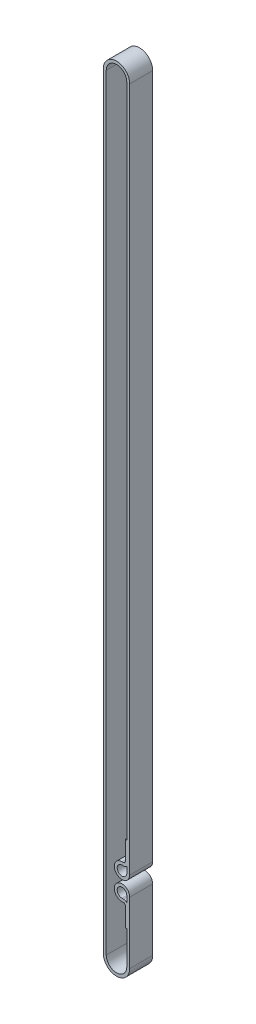
SolidWorks part; units mm, degrees
ref_plane "Front Plane" through (0, 0, 0) normal (0, 0, 1) x (1, 0, 0)
ref_plane "Top Plane" through (0, 0, 0) normal (0, 1, 0) x (1, 0, 0)
ref_plane "Right Plane" through (0, 0, 0) normal (1, 0, 0) x (0, 0, -1)
sketch "Sketch1" plane through (0, 0, 0) normal (0, 0, 1) x (1, 0, 0)
  line L0 (-6.365, 0) -> (-6.365, -400)
  line L1 (6.365, -400) -> (6.365, -367.7)
  line L2 (5.107, -382.704) -> (5.107, -372.704)
  line L3 (2.861, -357.7) -> (2.861, -367.7) construction
  line L4 (6.365, -357.7) -> (6.365, 0)
  line L5 (2.861, -371.204) -> (3.607, -371.204)
  line L6 (-997.139, -362.7) -> (49002.861, -362.7) construction
  line L7 (5.107, -342.696) -> (5.107, -352.696)
  line L8 (2.861, -354.196) -> (3.607, -354.196)
  arc A0 (6.365, 0) -> (-6.365, 0) centre (0, 0) ccw
  arc A1 (-6.365, -400) -> (6.365, -400) centre (0, -400) ccw
  circle A2 centre (2.861, -367.7) radius 2.5 construction
  arc A3 (6.365, -367.7) -> (2.861, -371.204) centre (2.861, -367.7) ccw
  arc A4 (3.607, -371.204) -> (5.107, -372.704) centre (3.607, -372.704) cw
  circle A5 centre (2.861, -357.7) radius 2.5 construction
  arc A6 (3.607, -354.196) -> (5.107, -352.696) centre (3.607, -352.696) ccw
  arc A7 (6.365, -357.7) -> (2.861, -354.196) centre (2.861, -357.7) cw
  point P11 (5.361, -367.7)
  point P22 (2.861, -362.7)
  dimension "D1" = 12.73
  dimension "D3" = 5
  dimension "D7" = 1.5
  dimension "D2" = 400
  dimension "D4" = 32.3
  dimension "D5" = 1.004
  dimension "D6" = 1.258
  dimension "D8" = 10
  dimension "D10" = 10
extrude "Extrude-Thin1" add sketch "Sketch1" along normal blind 12 thin
sketch "Sketch3" plane through (0, 0, 12) normal (0, 0, 1) x (1, 0, 0)
  line L11 (5.361, -367.7) -> (5.361, -370.917)
  line L12 (3.607, -370.2) -> (2.861, -370.2)
  line L13 (5.361, -367.7) -> (5.361, -370.917)
  line L14 (2.861, -355.2) -> (3.607, -355.2)
  line L15 (5.361, -354.483) -> (5.361, -357.7)
  line L16 (2.861, -355.2) -> (3.607, -355.2)
  line L17 (5.361, -354.483) -> (5.361, -357.7)
  line L18 (3.607, -370.2) -> (2.861, -370.2)
  line L20 (5.107, -352.696) -> (5.107, -342.696) construction
  line L21 (2.861, -354.196) -> (3.607, -354.196) construction
  line L22 (6.365, 0) -> (6.365, -357.7) construction
  line L23 (5.361, 0) -> (5.361, -357.7)
  line L24 (-5.361, -400) -> (-5.361, 0)
  line L25 (5.361, -367.7) -> (5.361, -400)
  line L26 (5.361, 0) -> (5.361, -342.696)
  line L27 (-5.361, -400) -> (-5.361, 0)
  line L28 (5.361, -367.7) -> (5.361, -370.917)
  line L29 (-6.365, -400) -> (-6.365, 0) construction
  line L30 (5.107, -382.704) -> (5.107, -372.704) construction
  line L31 (3.607, -371.204) -> (2.861, -371.204) construction
  line L32 (6.365, -367.7) -> (6.365, -400) construction
  line L33 (5.107, -352.696) -> (5.107, -342.696)
  line L34 (2.861, -354.196) -> (3.607, -354.196)
  line L35 (6.365, 0) -> (6.365, -357.7)
  line L36 (-6.365, -400) -> (-6.365, 0)
  line L37 (5.107, -382.704) -> (5.107, -372.704)
  line L38 (3.607, -371.204) -> (2.861, -371.204)
  line L39 (6.365, -367.7) -> (6.365, -400)
  line L40 (5.107, -342.696) -> (5.361, -342.696)
  line L41 (5.361, -354.483) -> (5.361, -357.7)
  line L42 (5.107, -382.704) -> (5.361, -382.704)
  line L43 (5.361, -382.704) -> (5.361, -400)
  arc A10 (5.361, -370.917) -> (3.607, -370.2) centre (3.607, -372.704) ccw
  arc A11 (5.361, -367.7) -> (2.861, -370.2) centre (2.861, -367.7) ccw
  arc A12 (3.607, -355.2) -> (5.361, -354.483) centre (3.607, -352.696) ccw
  arc A13 (2.861, -355.2) -> (5.361, -357.7) centre (2.861, -357.7) ccw
  arc A14 (3.607, -355.2) -> (5.361, -354.483) centre (3.607, -352.696) ccw
  arc A15 (2.861, -355.2) -> (5.361, -357.7) centre (2.861, -357.7) ccw
  arc A16 (5.361, -370.917) -> (3.607, -370.2) centre (3.607, -372.704) ccw
  arc A17 (5.361, -367.7) -> (2.861, -370.2) centre (2.861, -367.7) ccw
  arc A18 (3.607, -354.196) -> (5.107, -352.696) centre (3.607, -352.696) ccw construction
  arc A19 (2.861, -354.196) -> (6.365, -357.7) centre (2.861, -357.7) ccw construction
  arc A20 (5.361, 0) -> (-5.361, 0) centre (0, 0) ccw
  arc A21 (-5.361, -400) -> (5.361, -400) centre (0, -400) ccw
  arc A22 (5.361, 0) -> (-5.361, 0) centre (0, 0) ccw
  arc A23 (-5.361, -400) -> (5.361, -400) centre (0, -400) ccw
  arc A24 (6.365, 0) -> (-6.365, 0) centre (0, 0) ccw construction
  arc A25 (-6.365, -400) -> (6.365, -400) centre (0, -400) ccw construction
  arc A26 (5.107, -372.704) -> (3.607, -371.204) centre (3.607, -372.704) ccw construction
  arc A27 (6.365, -367.7) -> (2.861, -371.204) centre (2.861, -367.7) ccw construction
  arc A28 (3.607, -354.196) -> (5.107, -352.696) centre (3.607, -352.696) ccw
  arc A29 (2.861, -354.196) -> (6.365, -357.7) centre (2.861, -357.7) ccw
  arc A30 (6.365, 0) -> (-6.365, 0) centre (0, 0) ccw
  arc A31 (-6.365, -400) -> (6.365, -400) centre (0, -400) ccw
  arc A32 (5.107, -372.704) -> (3.607, -371.204) centre (3.607, -372.704) ccw
  arc A33 (6.365, -367.7) -> (2.861, -371.204) centre (2.861, -367.7) ccw
  line M14 (5.107, -352.696) -> (5.107, -342.696)
  line M30 (5.107, -382.704) -> (5.107, -372.704)
  arc M31 (5.107, -372.704) -> (3.607, -371.204) centre (3.607, -372.704) ccw
  line M32 (3.607, -371.204) -> (2.861, -371.204)
  arc M33 (2.861, -371.204) -> (6.365, -367.7) centre (2.861, -367.7) cw
  line M34 (6.365, -367.7) -> (6.365, -400)
  arc M35 (6.365, -400) -> (-6.365, -400) centre (0, -400) cw
  line M36 (-6.365, -400) -> (-6.365, 0)
  arc M37 (-6.365, 0) -> (6.365, 0) centre (0, 0) cw
  line M38 (6.365, 0) -> (6.365, -357.7)
  arc M39 (6.365, -357.7) -> (2.861, -354.196) centre (2.861, -357.7) cw
  line M40 (2.861, -354.196) -> (3.607, -354.196)
  arc M41 (3.607, -354.196) -> (5.107, -352.696) centre (3.607, -352.696) ccw
  dimension "D1" = 1.004
  dimension "D2" = 1.004
  dimension "D3" = 1.004
extrude "Boss-Extrude2" add sketch "Sketch3" against normal up to surface (12 mm away) contours A23 L27 A22 L26 L40 L42 L43 A17 L13 A16 L18 A15 L16 A14 L17 M14 M41 M40 M39 M38 M37 M36 M35 M34 M33 M32 M31 M30 up to face at (2.6436, -316.2143, 0)
